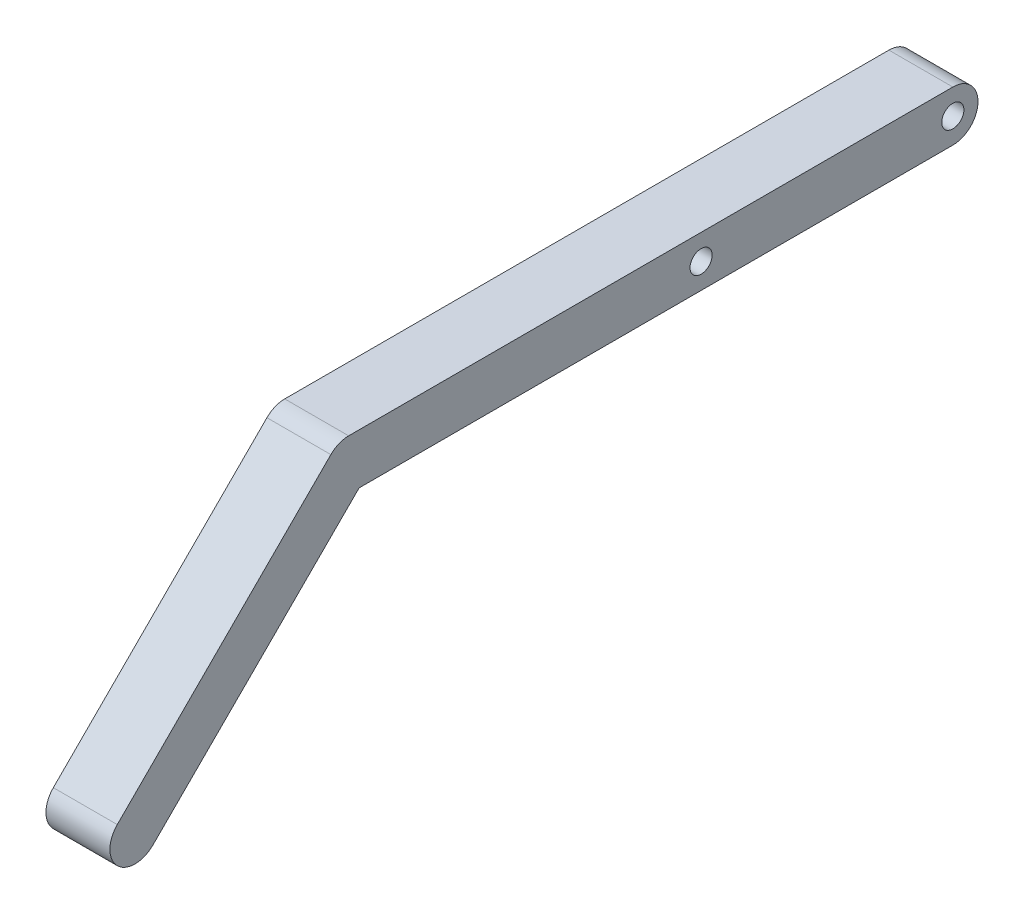
SolidWorks part; units mm, degrees
ref_plane "Front Plane" through (0, 0, 0) normal (0, 0, 1) x (1, 0, 0)
ref_plane "Top Plane" through (0, 0, 0) normal (0, 1, 0) x (1, 0, 0)
ref_plane "Right Plane" through (0, 0, 0) normal (1, 0, 0) x (0, 0, -1)
sketch "Sketch1" plane through (0, 0, 0) normal (1, 0, 0) x (0, 0, -1)
  line L0 (0, 0) -> (45, 150) construction
  line L5 (45, 150) -> (-75, 150)
  line L6 (-210, 110) -> (-60, 110) construction
  line L7 (-210, 110) -> (-210, 28) construction
  line L8 (-210, 28) -> (-60, 28) construction
  line L9 (-60, 110) -> (-60, 28) construction
  line L10 (-210, 28) -> (-60, 28) construction
  line L11 (-210, 28) -> (-210, -20) construction
  line L12 (-210, -20) -> (-60, -20) construction
  line L13 (-60, 28) -> (-60, -20) construction
  line L14 (-75, 150) -> (-117.4264, 107.5736)
  line L15 (-60, 110) -> (-34.6, 68) construction
  line L16 (-34.6, 68) -> (-34.6, 28) construction
  line L17 (-34.6, 28) -> (-60, 28) construction
  circle A0 centre (0, 0) radius 2.25
  point P3 (-5, 150)
  dimension "D4" = 4.5
  dimension "D1" = 156.6046
  dimension "D2" = 150
  dimension "D3" = 82
  dimension "D5" = 130
  dimension "D6" = 135
  dimension "D7" = 50
  dimension "D8" = 150
  dimension "D9" = 5
  dimension "D10" = 60
  dimension "D11" = 120
  dimension "D12" = 20
  dimension "D13" = 60
  dimension "D14" = 25.4
  dimension "D15" = 40
sketch "Sketch2" plane through (0, 0, 0) normal (1, 0, 0) x (0, 0, -1)
  line L0 (-75, 155) -> (45, 155)
  line L1 (-120.9619, 111.1091) -> (-78.5355, 153.5355)
  line L2 (-113.8909, 104.0381) -> (-72.9289, 145)
  line L3 (45, 145) -> (-72.9289, 145)
  arc A0 (45, 145) -> (45, 155) centre (45, 150) ccw
  circle A1 centre (-5, 150) radius 2.2
  arc A2 (-75, 155) -> (-78.5355, 153.5355) centre (-75, 150) ccw
  arc A3 (-120.9619, 111.1091) -> (-113.8909, 104.0381) centre (-117.4264, 107.5736) ccw
  circle A4 centre (45, 150) radius 2.2
  dimension "D1" = 5
  dimension "D2" = 4.4
  dimension "D3" = 10
extrude "Boss-Extrude1" add sketch "Sketch2" along normal blind 12.7
